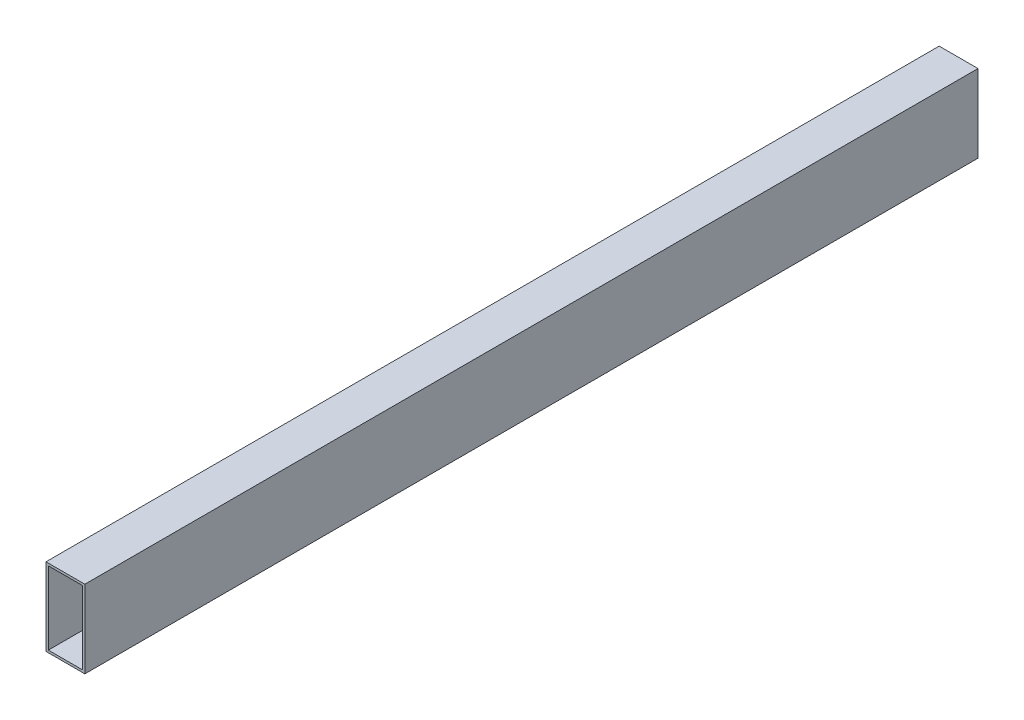
SolidWorks part; units mm, degrees
ref_plane "Front Plane" through (0, 0, 0) normal (0, 0, 1) x (1, 0, 0)
ref_plane "Top Plane" through (0, 0, 0) normal (0, 1, 0) x (1, 0, 0)
ref_plane "Right Plane" through (0, 0, 0) normal (1, 0, 0) x (0, 0, -1)
sketch "Sketch2" plane through (0, 0, 0) normal (0, 0, 1) x (1, 0, 0)
  line L1 (-25.4, 50.8) -> (0, 50.8)
  line L2 (-25.4, 50.8) -> (-25.4, 0)
  line L3 (-25.4, 0) -> (0, 0)
  line L4 (0, 50.8) -> (0, 0)
  dimension "D1" = 50.8
  dimension "D2" = 25.4
extrude "Extrude-Thin1" add sketch "Sketch2" along normal blind 584.2 thin
